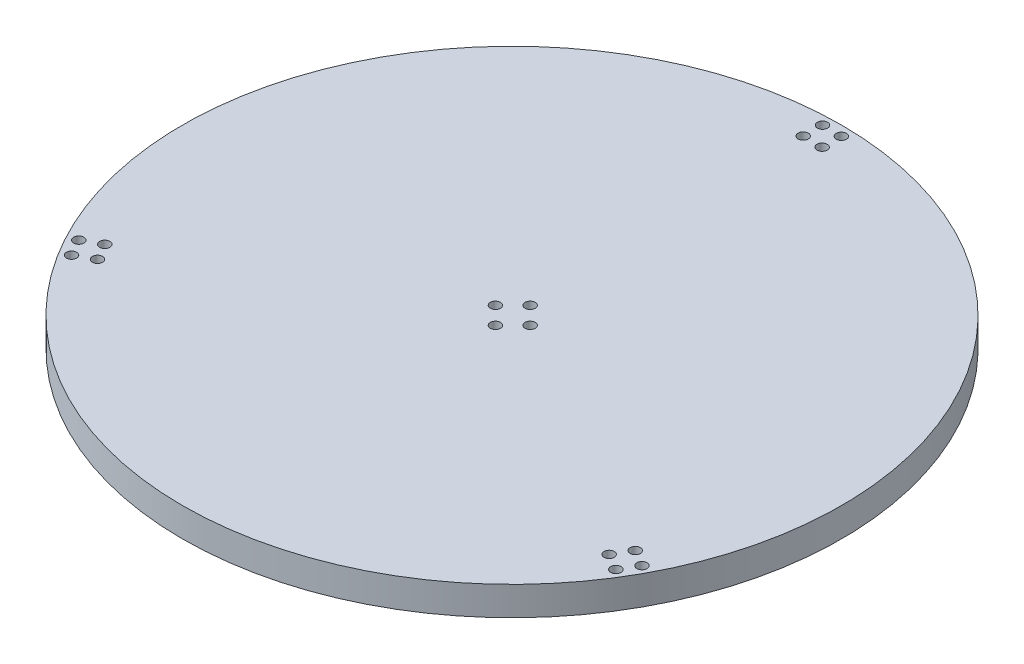
SolidWorks part; units mm, degrees
ref_plane "Front Plane" through (0, 0, 0) normal (0, 0, 1) x (1, 0, 0)
ref_plane "Top Plane" through (0, 0, 0) normal (0, 1, 0) x (1, 0, 0)
ref_plane "Right Plane" through (0, 0, 0) normal (1, 0, 0) x (0, 0, -1)
sketch "Sketch2" plane through (0, 0, 0) normal (0, 1, 0) x (1, 0, 0)
  circle A0 centre (0, 0) radius 217.17
  dimension "D1" = 434.34
extrude "Boss-Extrude1" add sketch "Sketch2" along normal blind 19.05
sketch "Sketch3" plane through (0, 19.05, 0) normal (0, 1, 0) x (1, 0, 0)
  line L0 (0, 0) -> (6.2179, 198.1163) construction
  line L1 (0.2675, 0.2512) -> (0.2675, -11.1788) construction
  circle A0 centre (0, 0) radius 204.47 construction
  circle A1 centre (0, 204.47) radius 8.89 construction
  circle A2 centre (-6.2179, 210.8237) radius 3.3782
  circle A3 centre (6.3537, 210.6879) radius 3.3782
  circle A4 centre (6.2179, 198.1163) radius 3.3782
  circle A5 centre (-6.3537, 198.2521) radius 3.3782
  circle A10 centre (185.6876, -100.027) radius 3.3782
  circle A15 centre (179.2842, -110.8464) radius 3.3782
  circle A16 centre (0.2675, 0.2512) radius 11.43 construction
  circle A21 centre (0.2675, -11.1788) radius 3.3782
  circle A22 centre (-11.1625, 0.2512) radius 3.3782
  circle A23 centre (0.2675, 11.6812) radius 3.3782
  circle A24 centre (11.6975, 0.2512) radius 3.3782
  circle A25 centre (168.4648, -104.443) radius 3.3782
  circle A26 centre (174.8682, -93.6236) radius 3.3782
  circle A27 centre (177.0762, -102.235) radius 8.89 construction
  circle A28 centre (-179.4697, -110.7967) radius 3.3782
  circle A29 centre (-185.6379, -99.8415) radius 3.3782
  circle A30 centre (-174.6827, -93.6733) radius 3.3782
  circle A31 centre (-168.5145, -104.6285) radius 3.3782
  circle A32 centre (-177.0762, -102.235) radius 8.89 construction
  point P16 (0, 204.47)
  point P29 (177.0762, -102.235)
  point P41 (-177.0762, -102.235)
  dimension "D1" = 408.94
  dimension "D2" = 17.78
  dimension "D3" = 6.7564
  dimension "D7" = 22.86
  dimension "D8" = 6.7564
  dimension "D6" = 198.2138
  dimension "D10" = 11.43
  dimension "D4" = 4
  dimension "D9" = 4
  dimension "D5" = 3
extrude "Cut-Extrude1" cut sketch "Sketch3" against normal blind 19.05
